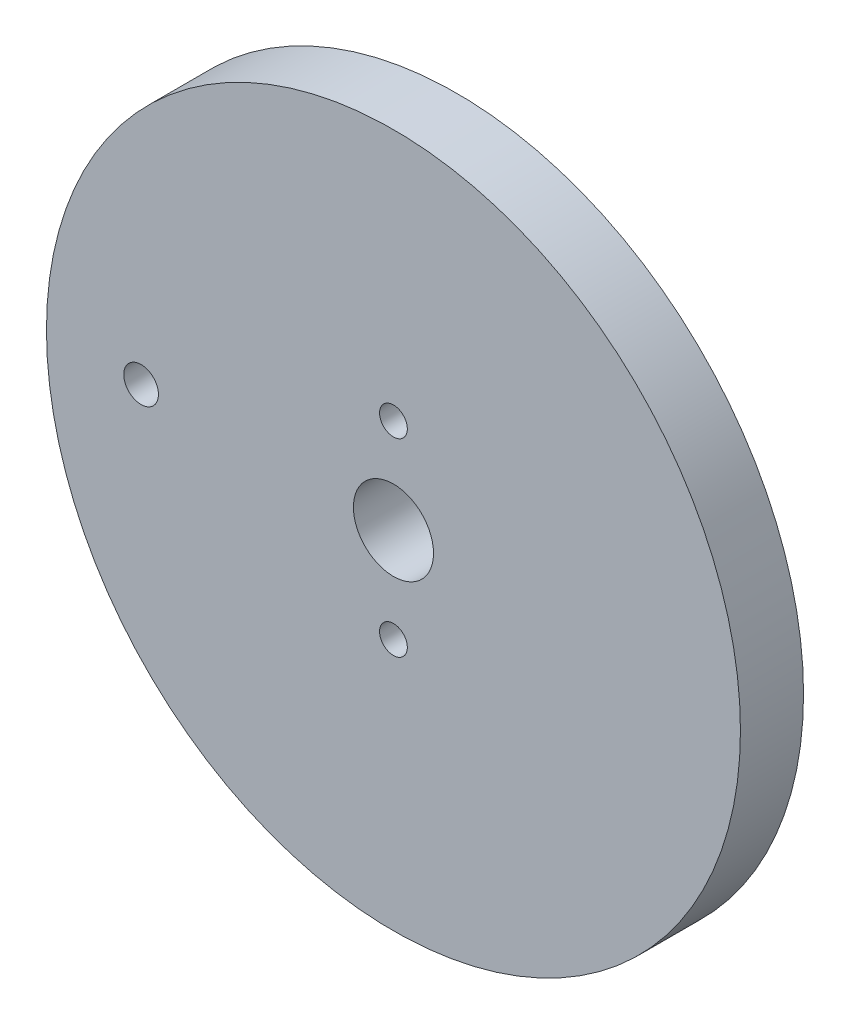
SolidWorks part; units mm, degrees
material "6061 Alloy"
ref_plane "Front Plane" through (0, 0, 0) normal (0, 0, 1) x (1, 0, 0)
ref_plane "Top Plane" through (0, 0, 0) normal (0, 1, 0) x (1, 0, 0)
ref_plane "Right Plane" through (0, 0, 0) normal (1, 0, 0) x (0, 0, -1)
sketch "Sketch1" plane through (0, 0, 0) normal (0, 0, 1) x (1, 0, 0)
  circle A0 centre (0, 0) radius 55
  dimension "D1" = 110
extrude "3/8" add sketch "Sketch1" along normal blind 10
sketch "Sketch2" [suppressed] plane through (0, 0, 10) normal (0, 0, 1) x (1, 0, 0)
  line L0 (0, 0) -> (0, 55) construction
  line L1 (-1.3148, 74.311) -> (0, 76.3551) construction
  line L3 (-20.0506, 46) -> (-20.0506, 29.25)
  line L4 (-20.0506, 29.25) -> (19.9494, 29.25)
  line L5 (19.9494, 46) -> (19.9494, 29.25)
  line L6 (0, 0) -> (0, 55) construction
  line L7 (-20.0506, 37.625) -> (19.9494, 37.625) construction
  line L8 (-30.1496, 76.3551) -> (30.1496, 76.3551)
  line L9 (-30.1496, 76.3551) -> (-30.1496, 46)
  line L10 (-30.1496, 46) -> (-20.0506, 46)
  line L11 (30.1496, 76.3551) -> (30.1496, 46)
  line L12 (19.9494, 46) -> (30.1496, 46)
  line L13 (-30.1496, 61.1776) -> (30.1496, 61.1776) construction
  circle A0 centre (0, 0) radius 55 construction
  point P6 (0, 37.625)
  point P130 (-0.1244, 61.1776)
  dimension "D1" = 40
  dimension "D2" = 29.25
  dimension "D3" = 46
extrude "Cut-Extrude1" [suppressed] cut sketch "Sketch2" against normal up to surface (10 mm away)
sketch "Sketch5" plane through (0, 0, 10) normal (0, 0, 1) x (1, 0, 0)
  circle A0 centre (0, 0) radius 6.35
  dimension "D1" = 12.7
extrude "Cut-Extrude2" cut sketch "Sketch5" against normal up to surface (10 mm away) up to face at (55, 0, 0)
sketch "Sketch6" plane through (0, 0, 10) normal (0, 0, 1) x (1, 0, 0)
  circle A0 centre (0, 0) radius 15 construction
  circle A1 centre (0, 15) radius 2.2
  circle A2 centre (0, -15) radius 2.2
  point P13 (0, 0)
  dimension "D1" = 30
  dimension "D2" = 4.4
  dimension "D3" = 2
extrude "M4_through2" cut sketch "Sketch6" against normal up to surface (10 mm away) up to face at (6.35, 0, 0)
sketch "Sketch7" plane through (0, 0, 10) normal (0, 0, 1) x (1, 0, 0)
  line L0 (0, 0) -> (0, 38.8961) construction
  line L1 (-40, 0) -> (-40, -25) construction
  circle A0 centre (-40, 0) radius 2.75
  circle A4 centre (0, 0) radius 30 construction
  dimension "D2" = 5.5
  dimension "D3" = 25
  dimension "D4" = 60
  dimension "D1" = 40
  dimension "D5" = 0
extrude "Cut-Extrude4" cut sketch "Sketch7" against normal blind 10
